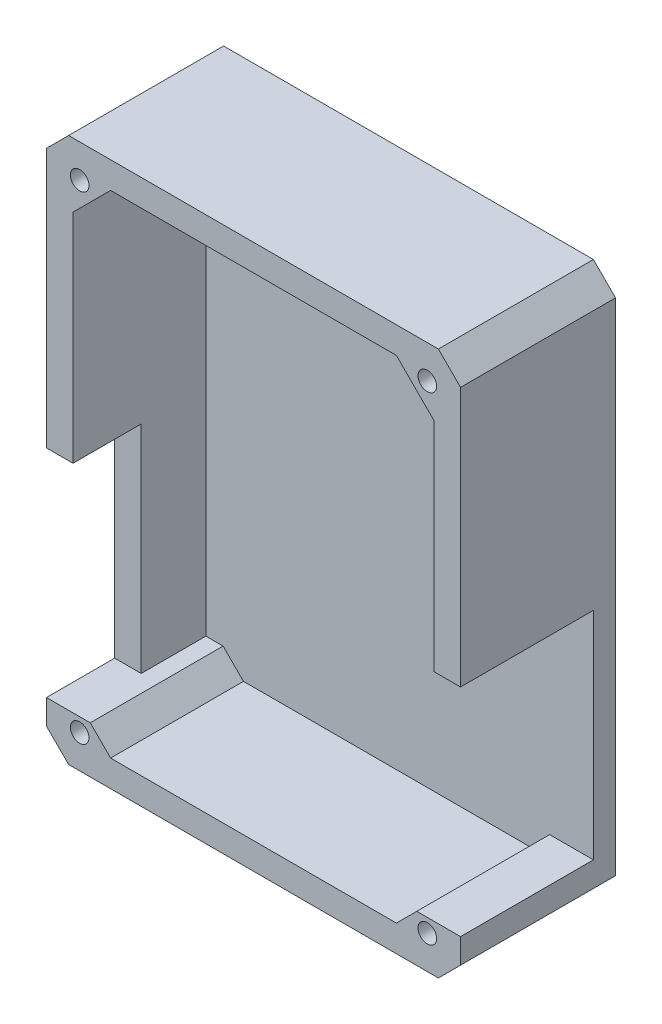
SolidWorks part; units mm, degrees
ref_plane "Front Plane" through (0, 0, 0) normal (0, 0, 1) x (1, 0, 0)
ref_plane "Top Plane" through (0, 0, 0) normal (0, 1, 0) x (1, 0, 0)
ref_plane "Right Plane" through (0, 0, 0) normal (1, 0, 0) x (0, 0, -1)
sketch "Sketch1" plane through (0, 0, 0) normal (0, 0, 1) x (1, 0, 0)
  line L12 (-46.75, -33) -> (46.75, -33)
  line L13 (-46.75, -33) -> (-46.75, 90)
  line L14 (-46.75, 90) -> (46.75, 90)
  line L15 (46.75, -33) -> (46.75, 90)
  dimension "D1" = 123
  dimension "D2" = 93.5
extrude "Boss-Extrude1" add sketch "Sketch1" along normal blind 5
sketch "Sketch3" plane through (0, 0, 5) normal (0, 0, 1) x (1, 0, 0)
  line L0 (-46.75, 26.4) -> (-40.75, 26.4)
  line L1 (-46.75, 90) -> (-46.75, -33) construction
  line L2 (-40.75, 26.4) -> (-40.75, 84)
  line L3 (-40.75, 84) -> (40.75, 84)
  line L4 (40.75, 84) -> (40.75, 26.4)
  line L5 (40.75, 26.4) -> (46.75, 26.4)
  line L6 (46.75, -33) -> (46.75, 90) construction
  line L7 (46.75, 26.4) -> (46.75, 90)
  line L8 (46.75, 90) -> (-46.75, 90)
  line L9 (-46.75, 90) -> (-46.75, 26.4)
  line L10 (-46.75, -33) -> (-46.75, -22.4)
  line L11 (-46.75, -22.4) -> (-40.75, -22.4)
  line L12 (-40.75, -22.4) -> (-40.75, -27)
  line L13 (-40.75, -27) -> (40.75, -27)
  line L14 (40.75, -27) -> (40.75, -22.4)
  line L15 (40.75, -22.4) -> (46.75, -22.4)
  line L16 (46.75, -22.4) -> (46.75, -33)
  line L17 (46.75, -33) -> (-46.75, -33)
  line L18 (0, -33) -> (0, 90) construction
  line L19 (-40.75, 75.5147) -> (-32.2647, 84)
  line L20 (40.75, 75.5147) -> (32.2647, 84)
  line L21 (0, 28.5) -> (6.3358, 28.5) construction
  line L22 (-40.75, -18.5147) -> (-32.2647, -27)
  line L23 (40.75, -18.5147) -> (32.2647, -27)
  line L24 (-40.75, -22.4) -> (-36.8647, -22.4)
  line L25 (40.75, -22.4) -> (36.8647, -22.4)
  line M9 (-46.75, 90) -> (-46.75, -33)
  line M10 (-46.75, -33) -> (46.75, -33)
  line M11 (46.75, -33) -> (46.75, 90)
  line M12 (46.75, 90) -> (-46.75, 90)
  dimension "D1" = 6
  dimension "D2" = 6
  dimension "D3" = 6
  dimension "D4" = 6
  dimension "D5" = 6
  dimension "D6" = 6
  dimension "D7" = 48.8
  dimension "D8" = 48.8
  dimension "D9" = 10.6
  dimension "D10" = 10.6
  dimension "D11" = 45
  dimension "D12" = 12
extrude "Boss-Extrude2" add sketch "Sketch3" along normal blind 30 contours L15 L14 L13 L12 L11 M9 M10 M11 | L24 L12 L13 L22 | L14 L25 L23 L13 | L4 L5 L0 L2 L3 M11 M12 M9 | L20 L4 L3 | L2 L19 L3
chamfer "Chamfer1" distance 5 angle 45 4 edges at (46.75, 90, 17.5) (46.75, -33, 17.5) (-46.75, -33, 17.5) (-46.75, 90, 17.5)
sketch "Sketch4" plane through (0, 0, 5) normal (0, 0, 1) x (1, 0, 0)
  line L1 (-46.75, 26.4) -> (-40.75, 26.4)
  line L2 (-46.75, 26.4) -> (-46.75, -22.4)
  line L3 (-46.75, -22.4) -> (-40.75, -22.4)
  line L4 (-40.75, 26.4) -> (-40.75, -22.4)
  point P4 (-40.75, -22.4)
  point P5 (0, 0)
  point P7 (-40.75, 26.4)
  point P8 (0, 0)
  point P10 (-46.75, -22.4)
extrude "Boss-Extrude3" add sketch "Sketch4" along normal blind 14.6
sketch "Sketch5" plane through (0, 0, 35) normal (0, 0, 1) x (1, 0, 0)
  line L2 (0, 90) -> (0, 63.5343) construction
  line L3 (-46.75, -28) -> (-46.75, 85) construction
  line L4 (-46.75, 28.5) -> (-29.8219, 28.5) construction
  line L5 (41.75, 90) -> (-41.75, 90) construction
  circle A0 centre (-39.25, 82.5) radius 2.1
  circle A1 centre (-39.25, -25.5) radius 2.1
  circle A2 centre (39.25, 82.5) radius 2.1
  circle A3 centre (39.25, -25.5) radius 2.1
  point P20 (0, 90)
  point P21 (0, 90)
  point P24 (0, 0)
  point P25 (-46.75, 85)
  point P27 (0, 0)
  dimension "D1" = 7.5
  dimension "D2" = 4.2
  dimension "D3" = 7.5
extrude "Cut-Extrude1" cut sketch "Sketch5" against normal blind 3.5
sketch "Sketch6" plane through (0, 0, 0) normal (0, 0, -1) x (-1, 0, 0)
  line L0 (0, -33) -> (0, 49.1578) construction
  line L1 (41.75, -33) -> (-41.75, -33) construction
  line L2 (-33.3074, -33) -> (-33.3074, 32) construction
  circle A0 centre (-33.3074, -24) radius 2.1
  circle A1 centre (-33.3074, 32) radius 2.1
  circle A2 centre (33.3074, 32) radius 2.1
  circle A3 centre (33.3074, -24) radius 2.1
  dimension "D1" = 4.2
  dimension "D2" = 4.2
  dimension "D3" = 9
  dimension "D4" = 56
extrude "Cut-Extrude2" cut sketch "Sketch6" against normal blind 3.5
